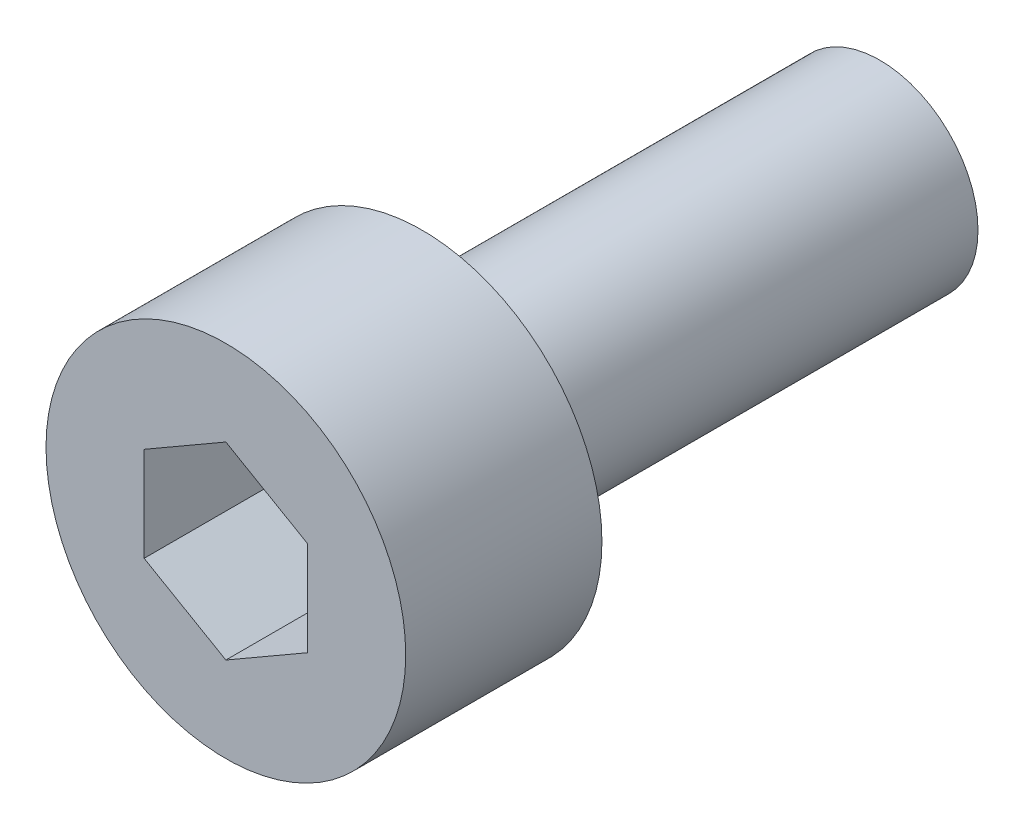
SolidWorks part; units mm, degrees
ref_plane "前视基准面" through (0, 0, 0) normal (0, 0, 1) x (1, 0, 0)
ref_plane "上视基准面" through (0, 0, 0) normal (0, 1, 0) x (1, 0, 0)
ref_plane "右视基准面" through (0, 0, 0) normal (1, 0, 0) x (0, 0, -1)
other "Configuration Table"
sketch "Profile_1" plane through (0, 0, 0) normal (0, 0, 1) x (1, 0, 0)
  circle A0 centre (0, 0) radius 1.5
extrude "Thread_envelope" add sketch "Profile_1" along normal blind 7 from offset 7
sketch "Profile_2" plane through (0, 0, 0) normal (0, 0, 1) x (1, 0, 0)
  line L0 (1.25, 0.7217) -> (0, 1.4434)
  line L1 (0, 1.4434) -> (-1.25, 0.7217)
  line L2 (-1.25, 0.7217) -> (-1.25, -0.7217)
  line L3 (-1.25, -0.7217) -> (0, -1.4434)
  line L4 (0, -1.4434) -> (1.25, -0.7217)
  line L5 (1.25, -0.7217) -> (1.25, 0.7217)
  circle A0 centre (0, 0) radius 2.75
extrude "Socket_head" add sketch "Profile_2" along normal blind 3 from offset 0
